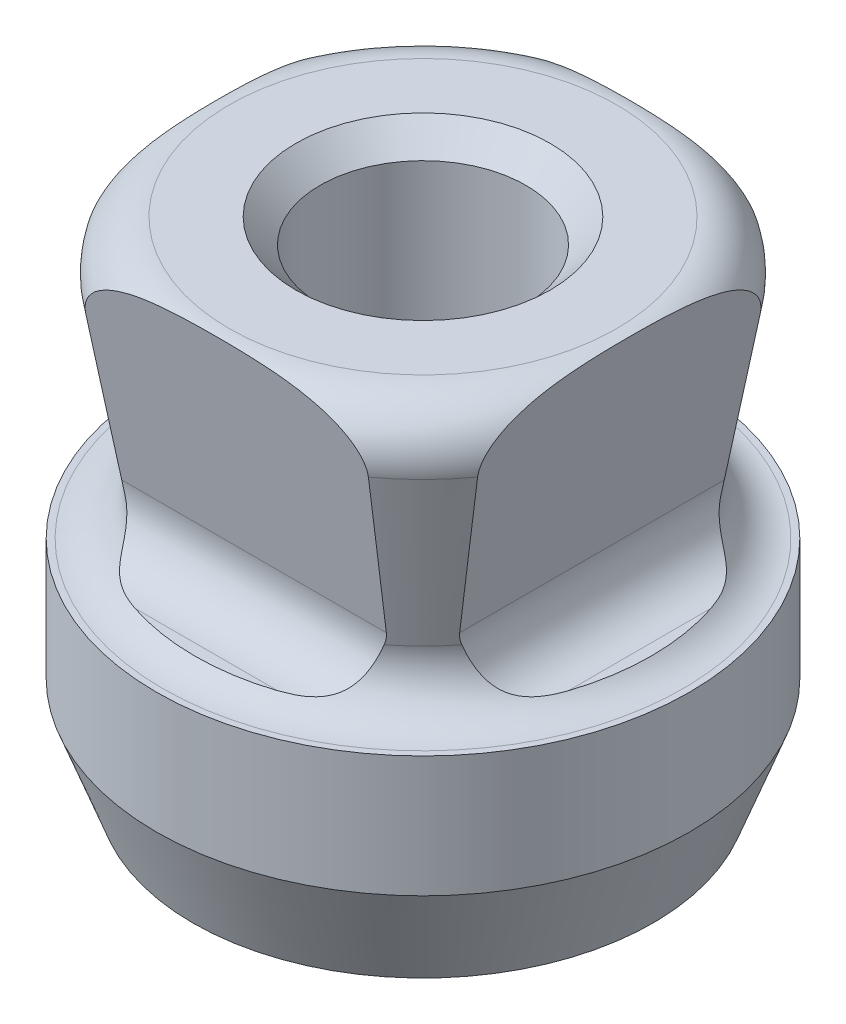
SolidWorks part; units mm, degrees
material "1.4021 (X20Cr13)"
ref_plane "Front Plane" through (0, 0, 0) normal (0, 0, 1) x (1, 0, 0)
ref_plane "Top Plane" through (0, 0, 0) normal (0, 1, 0) x (1, 0, 0)
ref_plane "Right Plane" through (0, 0, 0) normal (1, 0, 0) x (0, 0, -1)
sketch "Sketch1" plane through (0, 0, 0) normal (0, 0, 1) x (1, 0, 0)
  line L0 (0, 20.5) -> (-8, 20.5)
  line L1 (-8.75, 0) -> (0, 0) construction
  line L2 (0, 20.5) -> (0, 8.75)
  line L3 (0, 0) -> (0, 8.75) construction
  line L4 (-8.7696, 11.3473) -> (-9.9696, 18.1527)
  line L5 (-8.75, 0) -> (-9.5, 0)
  line L7 (-11, 4) -> (-11, 9)
  line L9 (-9.5, 0) -> (-11, 4)
  line L10 (0, 8.75) -> (-8.75, 0)
  line L19 (-10.7393, 9) -> (-11, 9)
  arc A0 (-8, 20.5) -> (-9.9696, 18.1527) centre (-8, 18.5) ccw
  arc A3 (-10.7393, 9) -> (-8.7696, 11.3473) centre (-10.7393, 11) ccw
  dimension "D1" = 2
  dimension "D3" = 0.75
  dimension "D5" = 8
  dimension "D2" = 8.75
  dimension "D4" = 8.75
  dimension "D6" = 8.7696
  dimension "D7" = 9.9696
  dimension "D8" = 4
  dimension "D9" = 11
  dimension "D10" = 9
revolve "Revolve1" add sketch "Sketch1" angle 360 about L2
cosmetic thread "Cosmetic Thread1" parameters "D2"=20.92
sketch "Sketch2" plane through (0, 20.5, 0) normal (0, 1, 0) x (1, 0, 0)
  circle A0 centre (0, 0) radius 4.25
  dimension "D1" = 8.5
extrude "Cut-Extrude1" cut sketch "Sketch2" against normal through all
chamfer "Chamfer1" distance 1 angle 45 1 edges at (0, 20.5, 4.25)
sketch "Sketch3" plane through (0, 0, 0) normal (1, 0, 0) x (0, 0, -1)
  line L0 (-8.5, 20.5) -> (-6.9743, 11.8473)
  line L1 (8, 20.5) -> (-8, 20.5) construction
  line L2 (-13.5, 9.5) -> (-8.9439, 9.5)
  line L4 (-13.5, 9.5) -> (-13.5, 20.5)
  line L5 (-13.5, 20.5) -> (-8.5, 20.5)
  arc A0 (-8.9439, 9.5) -> (-6.9743, 11.8473) centre (-8.9439, 11.5) ccw
  dimension "D1" = 4
  dimension "D2" = 8.5
  dimension "D3" = 80
  dimension "D4" = 11
  dimension "D5" = 5
extrude "Cut-Extrude2" cut sketch "Sketch3" against normal through all both and the other way through all
pattern_circular "CirPattern1" count 4 over 360 about axis through (0, 0, 0) along (0, 1, 0) of "Cut-Extrude2"
